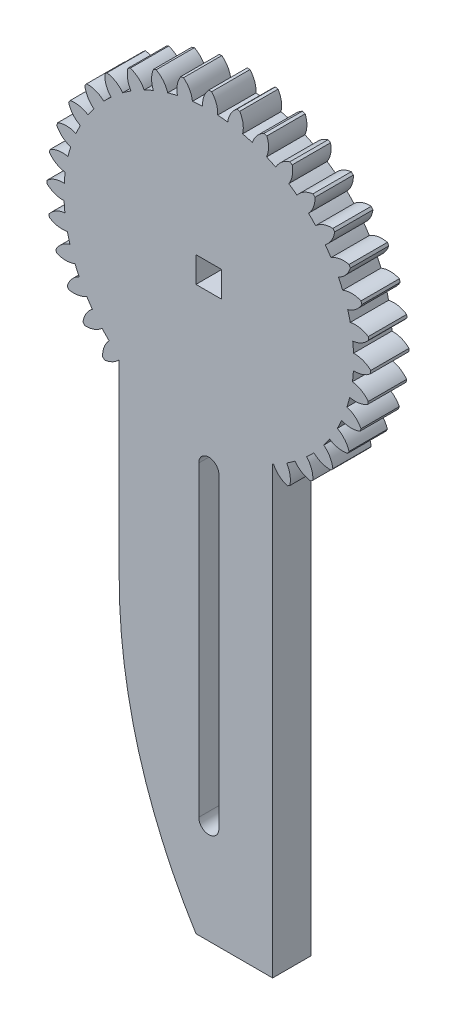
SolidWorks part; units mm, degrees
ref_plane "Front Plane" through (0, 0, 0) normal (0, 0, 1) x (1, 0, 0)
ref_plane "Top Plane" through (0, 0, 0) normal (0, 1, 0) x (1, 0, 0)
ref_plane "Right Plane" through (0, 0, 0) normal (1, 0, 0) x (0, 0, -1)
sketch "Sketch3" plane through (0, 0, 0) normal (0, 0, 1) x (1, 0, 0)
  line L1 (-1.6, -1.6) -> (1.6, -1.6)
  line L2 (-1.6, -1.6) -> (-1.6, 1.6)
  line L3 (-1.6, 1.6) -> (1.6, 1.6)
  line L4 (1.6, -1.6) -> (1.6, 1.6)
  line L5 (-1.6, -1.6) -> (1.6, 1.6) construction
  line L6 (-1.6, 1.6) -> (1.6, -1.6) construction
  line L10 (-1.6002, -71.4248) -> (7.9248, -71.4248)
  line L11 (7.9248, -12.7) -> (7.9248, -71.4248)
  line L13 (-11.1252, -12.7) -> (-11.1252, -38.1)
  line L14 (0, 0) -> (0, -12.7) construction
  line L16 (7.9248, -12.7) -> (-11.1252, -12.7)
  arc A0 (-11.1252, -38.1) -> (-1.6002, -71.4248) centre (51.9335, -38.1) ccw
  point P0 (0, 0)
  arc B0 (-17.1536, 5.4085) -> (-17.489, 4.1987) centre (0, 0) ccw
  arc B1 (-17.8704, -2.0361) -> (-19.8566, -3.145) centre (-17.5364, -4.9676) ccw
  arc B2 (-19.7987, -3.491) -> (-17.5597, -3.8929) centre (-18.1983, -1.0124) ccw
  arc B3 (-17.5597, -3.8929) -> (-17.2453, -5.1083) centre (0, 0) ccw
  arc B4 (-17.9525, 1.098) -> (-20.101, 0.3509) centre (-18.1326, -1.8469) ccw
  arc B5 (-17.8321, 2.3476) -> (-17.9525, 1.098) centre (0, 0) ccw
  arc B6 (-17.489, 4.1987) -> (-19.7347, 3.836) centre (-18.1778, 1.3298) ccw
  arc B7 (-19.7987, 3.491) -> (-17.8321, 2.3476) centre (-17.447, 5.2728) ccw
  arc B8 (-18.8917, 6.876) -> (-17.1536, 5.4085) centre (-16.2663, 8.2224) ccw
  arc B9 (-14.2693, 10.9492) -> (-14.9983, 9.9271) centre (0, 0) ccw
  arc B10 (-15.4006, 12.9227) -> (-14.2693, 10.9492) centre (-12.4731, 13.2899) ccw
  arc B11 (-15.1728, 13.1895) -> (-15.4006, 12.9227) centre (0, 0) ccw
  arc B12 (-13.0466, 12.3807) -> (-15.1728, 13.1895) centre (-15.0775, 10.2406) ccw
  arc B13 (-12.1512, 13.2607) -> (-13.0466, 12.3807) centre (0, 0) ccw
  arc B14 (-12.9227, 15.4006) -> (-12.1512, 13.2607) centre (-9.9759, 15.254) ccw
  arc B15 (-12.6519, 15.6238) -> (-12.9227, 15.4006) centre (0, 0) ccw
  arc B16 (-10.6985, 14.4582) -> (-12.6519, 15.6238) centre (-13.0702, 12.7032) ccw
  arc B17 (-9.6639, 15.1692) -> (-10.6985, 14.4582) centre (0, 0) ccw
  arc B18 (-10.0521, 17.4107) -> (-9.6639, 15.1692) centre (-7.1755, 16.7545) ccw
  arc B19 (-9.7467, 17.5834) -> (-10.0521, 17.4107) centre (0, 0) ccw
  arc B20 (-8.0253, 16.0963) -> (-9.7467, 17.5834) centre (-10.6658, 14.7798) ccw
  arc B21 (-6.8829, 16.6169) -> (-8.0253, 16.0963) centre (0, 0) ccw
  arc B22 (-6.876, 18.8917) -> (-6.8829, 16.6169) centre (-4.1571, 17.746) ccw
  arc B23 (-6.5453, 19.0088) -> (-6.876, 18.8917) centre (0, 0) ccw
  arc B24 (-5.1083, 17.2453) -> (-6.5453, 19.0088) centre (-7.9372, 16.4074) ccw
  arc B25 (-3.8929, 17.5597) -> (-5.1083, 17.2453) centre (0, 0) ccw
  arc B26 (-3.491, 19.7987) -> (-3.8929, 17.5597) centre (-1.0124, 18.1983) ccw
  arc B27 (-3.145, 19.8566) -> (-3.491, 19.7987) centre (0, 0) ccw
  arc B28 (-2.0361, 17.8704) -> (-3.145, 19.8566) centre (-4.9676, 17.5364) ccw
  arc B29 (-0.7845, 17.9689) -> (-2.0361, 17.8704) centre (0, 0) ccw
  arc B30 (0, 20.1041) -> (-0.7845, 17.9689) centre (2.1631, 18.0976) ccw
  arc B31 (0.3509, 20.101) -> (0, 20.1041) centre (0, 0) ccw
  arc B32 (1.098, 17.9525) -> (0.3509, 20.101) centre (-1.8469, 18.1326) ccw
  arc B33 (2.3476, 17.8321) -> (1.098, 17.9525) centre (0, 0) ccw
  arc B34 (3.491, 19.7987) -> (2.3476, 17.8321) centre (5.2728, 17.447) ccw
  arc B35 (3.836, 19.7347) -> (3.491, 19.7987) centre (0, 0) ccw
  arc B36 (4.1987, 17.489) -> (3.836, 19.7347) centre (1.3298, 18.1778) ccw
  arc B37 (5.4085, 17.1536) -> (4.1987, 17.489) centre (0, 0) ccw
  arc B38 (6.876, 18.8917) -> (5.4085, 17.1536) centre (8.2224, 16.2663) ccw
  arc B39 (7.2047, 18.7688) -> (6.876, 18.8917) centre (0, 0) ccw
  arc B40 (7.1719, 16.4942) -> (7.2047, 18.7688) centre (4.4662, 17.6707) ccw
  arc B41 (8.305, 15.9538) -> (7.1719, 16.4942) centre (0, 0) ccw
  arc B42 (10.052, 17.4107) -> (8.305, 15.9538) centre (10.9221, 14.5914) ccw
  arc B43 (10.3544, 17.2326) -> (10.052, 17.4107) centre (0, 0) ccw
  arc B44 (9.9271, 14.9983) -> (10.3544, 17.2326) centre (7.4668, 16.6267) ccw
  arc B45 (10.9492, 14.2693) -> (9.9271, 14.9983) centre (0, 0) ccw
  arc B46 (12.9227, 15.4006) -> (10.9492, 14.2693) centre (13.2899, 12.4731) ccw
  arc B47 (13.1895, 15.1728) -> (12.9227, 15.4006) centre (0, 0) ccw
  arc B48 (12.3807, 13.0466) -> (13.1895, 15.1728) centre (10.2406, 15.0775) ccw
  arc B49 (13.2607, 12.1512) -> (12.3807, 13.0466) centre (0, 0) ccw
  arc B50 (15.4006, 12.9227) -> (13.2607, 12.1512) centre (15.254, 9.9759) ccw
  arc B51 (15.6238, 12.6519) -> (15.4006, 12.9227) centre (0, 0) ccw
  arc B52 (14.4582, 10.6985) -> (15.6238, 12.6519) centre (12.7032, 13.0702) ccw
  arc B53 (15.1692, 9.6639) -> (14.4582, 10.6985) centre (0, 0) ccw
  arc B54 (17.4107, 10.0521) -> (15.1692, 9.6639) centre (16.7545, 7.1755) ccw
  arc B55 (17.5834, 9.7467) -> (17.4107, 10.0521) centre (0, 0) ccw
  arc B56 (16.0963, 8.0253) -> (17.5834, 9.7467) centre (14.7798, 10.6658) ccw
  arc B57 (16.6169, 6.8829) -> (16.0963, 8.0253) centre (0, 0) ccw
  arc B58 (18.8917, 6.876) -> (16.6169, 6.8829) centre (17.746, 4.1571) ccw
  arc B59 (19.0088, 6.5453) -> (18.8917, 6.876) centre (0, 0) ccw
  arc B60 (17.2453, 5.1083) -> (19.0088, 6.5453) centre (16.4074, 7.9372) ccw
  arc B61 (17.5597, 3.8929) -> (17.2453, 5.1083) centre (0, 0) ccw
  arc B62 (19.7987, 3.491) -> (17.5597, 3.8929) centre (18.1983, 1.0124) ccw
  arc B63 (19.8566, 3.145) -> (19.7987, 3.491) centre (0, 0) ccw
  arc B64 (17.8704, 2.0361) -> (19.8566, 3.145) centre (17.5364, 4.9676) ccw
  arc B65 (17.9689, 0.7845) -> (17.8704, 2.0361) centre (0, 0) ccw
  arc B66 (20.1041, 0) -> (17.9689, 0.7845) centre (18.0976, -2.1631) ccw
  arc B67 (20.101, -0.3509) -> (20.1041, 0) centre (0, 0) ccw
  arc B68 (17.9525, -1.098) -> (20.101, -0.3509) centre (18.1326, 1.8469) ccw
  arc B69 (17.8321, -2.3476) -> (17.9525, -1.098) centre (0, 0) ccw
  arc B70 (19.7987, -3.491) -> (17.8321, -2.3476) centre (17.447, -5.2728) ccw
  arc B71 (19.7347, -3.836) -> (19.7987, -3.491) centre (0, 0) ccw
  arc B72 (17.489, -4.1987) -> (19.7347, -3.836) centre (18.1778, -1.3298) ccw
  arc B73 (17.1536, -5.4085) -> (17.489, -4.1987) centre (0, 0) ccw
  arc B74 (18.8917, -6.876) -> (17.1536, -5.4085) centre (16.2663, -8.2224) ccw
  arc B75 (18.7688, -7.2047) -> (18.8917, -6.876) centre (0, 0) ccw
  arc B76 (16.4942, -7.1719) -> (18.7688, -7.2047) centre (17.6707, -4.4662) ccw
  arc B77 (15.9538, -8.305) -> (16.4942, -7.1719) centre (0, 0) ccw
  arc B78 (17.4107, -10.052) -> (15.9538, -8.305) centre (14.5914, -10.9221) ccw
  arc B79 (17.2326, -10.3544) -> (17.4107, -10.052) centre (0, 0) ccw
  arc B80 (14.9983, -9.9271) -> (17.2326, -10.3544) centre (16.6267, -7.4668) ccw
  arc B81 (14.2693, -10.9492) -> (14.9983, -9.9271) centre (0, 0) ccw
  arc B82 (15.4006, -12.9227) -> (14.2693, -10.9492) centre (12.4731, -13.2899) ccw
  arc B83 (15.1728, -13.1895) -> (15.4006, -12.9227) centre (0, 0) ccw
  arc B84 (13.0466, -12.3807) -> (15.1728, -13.1895) centre (15.0775, -10.2406) ccw
  arc B85 (12.1512, -13.2607) -> (13.0466, -12.3807) centre (0, 0) ccw
  arc B86 (12.9227, -15.4006) -> (12.1512, -13.2607) centre (9.9759, -15.254) ccw
  arc B87 (12.6519, -15.6238) -> (12.9227, -15.4006) centre (0, 0) ccw
  arc B88 (10.6985, -14.4582) -> (12.6519, -15.6238) centre (13.0702, -12.7032) ccw
  arc B89 (9.6639, -15.1692) -> (10.6985, -14.4582) centre (0, 0) ccw
  arc B90 (10.0521, -17.4107) -> (9.6639, -15.1692) centre (7.1755, -16.7545) ccw
  arc B91 (9.7467, -17.5834) -> (10.0521, -17.4107) centre (0, 0) ccw
  arc B92 (8.0253, -16.0963) -> (9.7467, -17.5834) centre (10.6658, -14.7798) ccw
  arc B93 (6.8829, -16.6169) -> (8.0253, -16.0963) centre (0, 0) ccw
  arc B94 (6.876, -18.8917) -> (6.8829, -16.6169) centre (4.1571, -17.746) ccw
  arc B95 (6.5453, -19.0088) -> (6.876, -18.8917) centre (0, 0) ccw
  arc B96 (5.1083, -17.2453) -> (6.5453, -19.0088) centre (7.9372, -16.4074) ccw
  arc B97 (3.8929, -17.5597) -> (5.1083, -17.2453) centre (0, 0) ccw
  arc B98 (3.491, -19.7987) -> (3.8929, -17.5597) centre (1.0124, -18.1983) ccw
  arc B99 (3.145, -19.8566) -> (3.491, -19.7987) centre (0, 0) ccw
  arc B100 (2.0361, -17.8704) -> (3.145, -19.8566) centre (4.9676, -17.5364) ccw
  arc B101 (0.7845, -17.9689) -> (2.0361, -17.8704) centre (0, 0) ccw
  arc B102 (0, -20.1041) -> (0.7845, -17.9689) centre (-2.1631, -18.0976) ccw
  arc B103 (-0.3509, -20.101) -> (0, -20.1041) centre (0, 0) ccw
  arc B104 (-1.098, -17.9525) -> (-0.3509, -20.101) centre (1.8469, -18.1326) ccw
  arc B105 (-2.3476, -17.8321) -> (-1.098, -17.9525) centre (0, 0) ccw
  arc B106 (-3.491, -19.7987) -> (-2.3476, -17.8321) centre (-5.2728, -17.447) ccw
  arc B107 (-3.836, -19.7347) -> (-3.491, -19.7987) centre (0, 0) ccw
  arc B108 (-4.1987, -17.489) -> (-3.836, -19.7347) centre (-1.3298, -18.1778) ccw
  arc B109 (-5.4085, -17.1536) -> (-4.1987, -17.489) centre (0, 0) ccw
  arc B110 (-6.876, -18.8917) -> (-5.4085, -17.1536) centre (-8.2224, -16.2663) ccw
  arc B111 (-7.2047, -18.7688) -> (-6.876, -18.8917) centre (0, 0) ccw
  arc B112 (-7.1719, -16.4942) -> (-7.2047, -18.7688) centre (-4.4662, -17.6707) ccw
  arc B113 (-8.305, -15.9538) -> (-7.1719, -16.4942) centre (0, 0) ccw
  arc B114 (-10.052, -17.4107) -> (-8.305, -15.9538) centre (-10.9221, -14.5914) ccw
  arc B115 (-10.3544, -17.2326) -> (-10.052, -17.4107) centre (0, 0) ccw
  arc B116 (-9.9271, -14.9983) -> (-10.3544, -17.2326) centre (-7.4668, -16.6267) ccw
  arc B117 (-10.9492, -14.2693) -> (-9.9271, -14.9983) centre (0, 0) ccw
  arc B118 (-12.9227, -15.4006) -> (-10.9492, -14.2693) centre (-13.2899, -12.4731) ccw
  arc B119 (-13.1895, -15.1728) -> (-12.9227, -15.4006) centre (0, 0) ccw
  arc B120 (-12.3807, -13.0466) -> (-13.1895, -15.1728) centre (-10.2406, -15.0775) ccw
  arc B121 (-13.2607, -12.1512) -> (-12.3807, -13.0466) centre (0, 0) ccw
  arc B122 (-15.4006, -12.9227) -> (-13.2607, -12.1512) centre (-15.254, -9.9759) ccw
  arc B123 (-15.6238, -12.6519) -> (-15.4006, -12.9227) centre (0, 0) ccw
  arc B124 (-14.4582, -10.6985) -> (-15.6238, -12.6519) centre (-12.7032, -13.0702) ccw
  arc B125 (-15.1692, -9.6639) -> (-14.4582, -10.6985) centre (0, 0) ccw
  arc B126 (-17.4107, -10.0521) -> (-15.1692, -9.6639) centre (-16.7545, -7.1755) ccw
  arc B127 (-17.5834, -9.7467) -> (-17.4107, -10.0521) centre (0, 0) ccw
  arc B128 (-16.0963, -8.0253) -> (-17.5834, -9.7467) centre (-14.7798, -10.6658) ccw
  arc B129 (-16.6169, -6.8829) -> (-16.0963, -8.0253) centre (0, 0) ccw
  arc B130 (-18.8917, -6.876) -> (-16.6169, -6.8829) centre (-17.746, -4.1571) ccw
  arc B131 (-19.0088, -6.5453) -> (-18.8917, -6.876) centre (0, 0) ccw
  arc B132 (-17.2453, -5.1083) -> (-19.0088, -6.5453) centre (-16.4074, -7.9372) ccw
  arc B133 (-19.8566, -3.145) -> (-19.7987, -3.491) centre (0, 0) ccw
  arc B134 (-17.9689, -0.7845) -> (-17.8704, -2.0361) centre (0, 0) ccw
  arc B135 (-20.1041, 0) -> (-17.9689, -0.7845) centre (-18.0976, 2.1631) ccw
  arc B136 (-20.101, 0.3509) -> (-20.1041, 0) centre (0, 0) ccw
  arc B137 (-19.7347, 3.836) -> (-19.7987, 3.491) centre (0, 0) ccw
  arc B138 (-18.7688, 7.2047) -> (-18.8917, 6.876) centre (0, 0) ccw
  arc B139 (-16.4942, 7.1719) -> (-18.7688, 7.2047) centre (-17.6707, 4.4662) ccw
  arc B140 (-15.9538, 8.305) -> (-16.4942, 7.1719) centre (0, 0) ccw
  arc B141 (-17.4107, 10.052) -> (-15.9538, 8.305) centre (-14.5914, 10.9221) ccw
  arc B142 (-17.2326, 10.3544) -> (-17.4107, 10.052) centre (0, 0) ccw
  arc B143 (-14.9983, 9.9271) -> (-17.2326, 10.3544) centre (-16.6267, 7.4668) ccw
sketch_block_instance "VEX-36-TOOTH-GEAR-b-1"
sketch_block "VEX-36-TOOTH-GEAR-b"
other "DetailItem3"
other "DetailItem4" parameters "D3"=5.08, "D2"=55.88, "D1"=3.0671, "D4"=36.7485, "D5"=18.9201, "D6"=63.0103, "D7"=9.525
extrude "Boss-Extrude2" add sketch "Sketch3" along normal blind 4.7625
sketch "Sketch4" plane through (0, 0, 4.7625) normal (0, 0, 1) x (1, 0, 0)
  circle A0 centre (0, 0) radius 2.2627
sketch "Sketch5" plane through (0, 0, 4.7625) normal (0, 0, 1) x (1, 0, 0)
  line L0 (0, -58.7248) -> (0, -20.6248) construction
  line L1 (-1.25, -58.7248) -> (-1.25, -20.6248)
  line L2 (1.25, -58.7248) -> (1.25, -20.6248)
  line L3 (-1.6002, -71.4248) -> (7.9248, -71.4248) construction
  arc A0 (-1.25, -58.7248) -> (1.25, -58.7248) centre (0, -58.7248) ccw
  arc A1 (1.25, -20.6248) -> (-1.25, -20.6248) centre (0, -20.6248) ccw
  point P3 (0, -39.6748)
  dimension "D1" = 2.5
  dimension "D2" = 12.7
  dimension "D3" = 38.1
extrude "Cut-Extrude1" cut sketch "Sketch5" against normal blind 10.16
